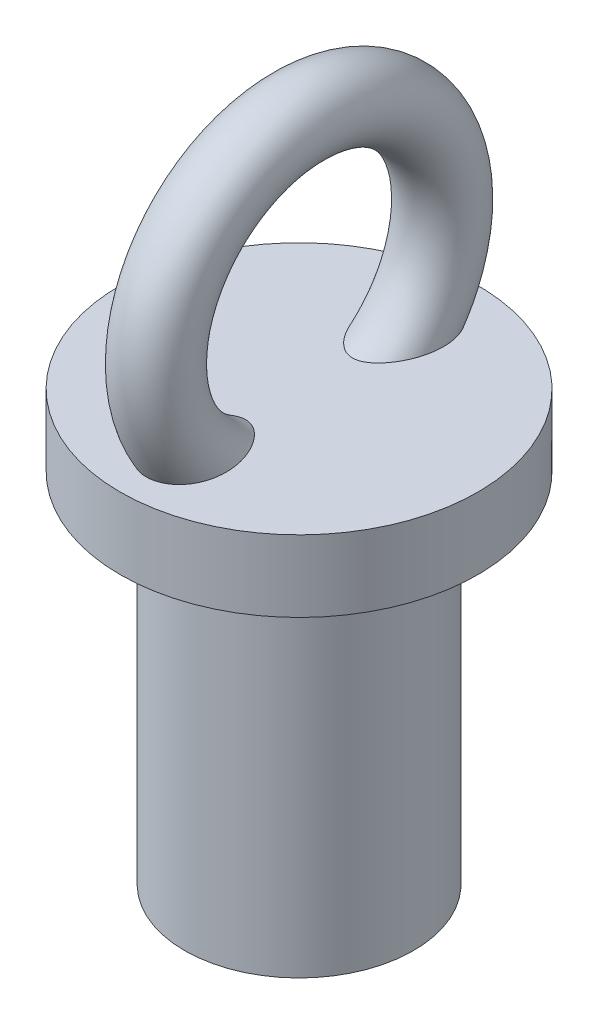
SolidWorks part; units mm, degrees
material "ASTM A36 Steel"
ref_plane "Front Plane" through (0, 0, 0) normal (0, 0, 1) x (1, 0, 0)
ref_plane "Top Plane" through (0, 0, 0) normal (0, 1, 0) x (1, 0, 0)
ref_plane "Right Plane" through (0, 0, 0) normal (1, 0, 0) x (0, 0, -1)
sketch "Sketch1" plane through (0, 0, 0) normal (0, 1, 0) x (1, 0, 0)
  circle A0 centre (0, 0) radius 8
  dimension "D1" = 16
extrude "Boss-Extrude1" add sketch "Sketch1" along normal blind 25
sketch "Sketch2" plane through (0, 25, 0) normal (0, 1, 0) x (1, 0, 0)
  circle A0 centre (0, 0) radius 12.5
  dimension "D1" = 25
extrude "Boss-Extrude2" add sketch "Sketch2" along normal blind 5
sketch "Sketch3" plane through (0, 0, 0) normal (1, 0, 0) x (0, 0, -1)
  arc A0 (4.9612, 27.8228) -> (-4.6928, 27.6748) centre (0, 36.5053) ccw
  dimension "D1" = 20
sketch "Sketch4" plane through (0, 0, 0) normal (0, 0, 1) x (1, 0, 0)
  line L0 (0, 27.6748) -> (0, 46.5053) construction
  circle A0 centre (0, 46.5053) radius 2.5
  dimension "D1" = 5
  dimension "D2" = 10
sweep "Sweep1" add profiles "Sketch4" path "Sketch3"
